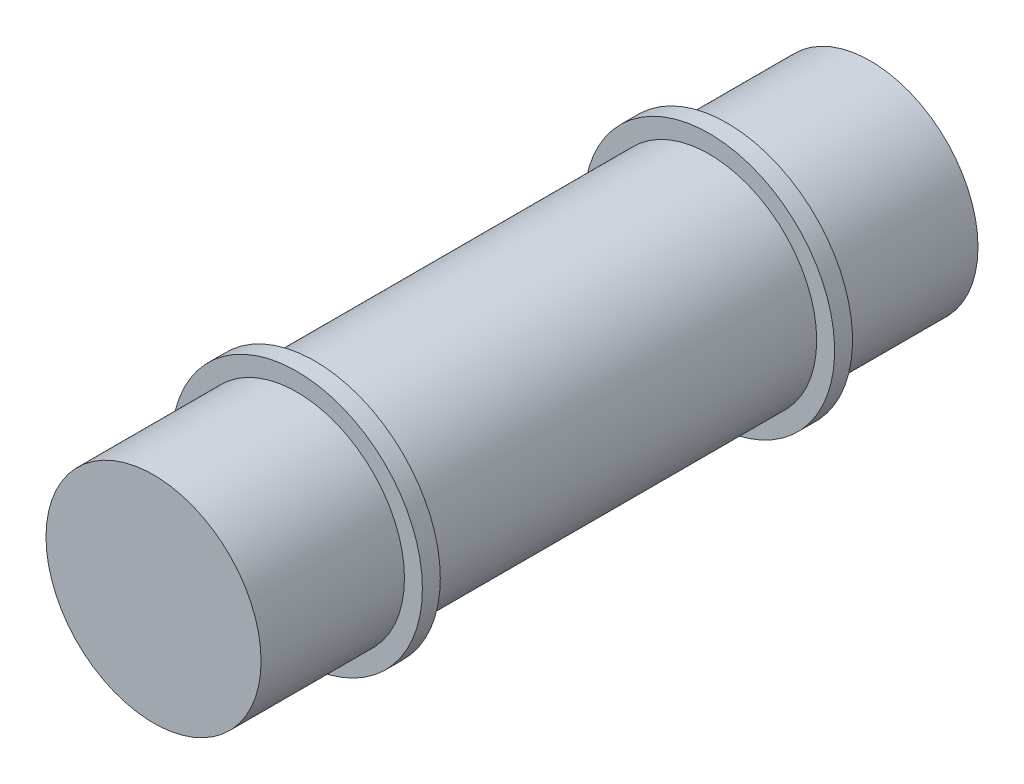
SolidWorks part; units mm, degrees
ref_plane "Plan de face" through (0, 0, 0) normal (0, 0, 1) x (1, 0, 0)
ref_plane "Plan de dessus" through (0, 0, 0) normal (0, 1, 0) x (1, 0, 0)
ref_plane "Plan de droite" through (0, 0, 0) normal (1, 0, 0) x (0, 0, -1)
sketch "Esquisse1" plane through (0, 0, 0) normal (0, 0, 1) x (1, 0, 0)
  circle A0 centre (0, 0) radius 6
  dimension "D1" = 12
extrude "Boss.-Extru.1" add sketch "Esquisse1" along normal blind 40
ref_plane "Plan1" through (0, 0, 8) normal (0, 0, -1) x (-1, 0, 0)
sketch "Esquisse2" plane through (0, 0, 8) normal (0, 0, -1) x (-1, 0, 0)
  circle A0 centre (0, 0) radius 6
  circle A1 centre (0, 0) radius 7
  dimension "D1" = 12
  dimension "D2" = 14
extrude "Boss.-Extru.2" add sketch "Esquisse2" against normal blind 1
ref_plane "Plan2" through (0, 0, 32) normal (0, 0, 1) x (1, 0, 0)
sketch "Esquisse3" plane through (0, 0, 32) normal (0, 0, 1) x (1, 0, 0)
  circle A0 centre (0, 0) radius 6
  circle A1 centre (0, 0) radius 7
  dimension "D1" = 12
  dimension "D2" = 14
extrude "Boss.-Extru.3" add sketch "Esquisse3" against normal blind 1
